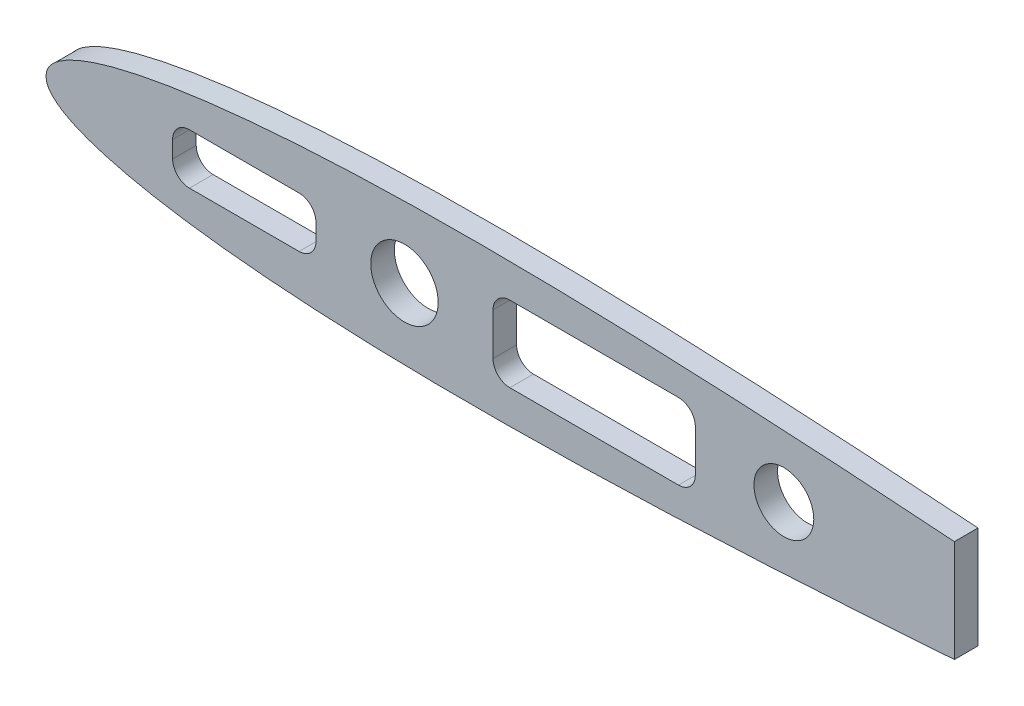
SolidWorks part; units mm, degrees
material "Фанера"
ref_plane "Front Plane" through (0, 0, 0) normal (0, 0, 1) x (1, 0, 0)
ref_plane "Top Plane" through (0, 0, 0) normal (0, 1, 0) x (1, 0, 0)
ref_plane "Right Plane" through (0, 0, 0) normal (1, 0, 0) x (0, 0, -1)
curve "Кривая1"
  spline degree 3 poles (110, 0, 0) (110.0276, -0.2367, 0) (110.0855, -0.7342, 0) (110.5302, -1.4271, 0) (111.1963, -2.0786, 0) (112.1098, -2.7013, 0) (113.2568, -3.2993, 0) (114.6379, -3.8731, 0) (116.2477, -4.4214, 0) (118.0813, -4.9426, 0) (120.1331, -5.4348, 0) (122.3972, -5.8961, 0) (124.8672, -6.3247, 0) (127.537, -6.7187, 0) (130.3997, -7.0764, 0) (133.4488, -7.3965, 0) (136.6771, -7.6776, 0) (140.0777, -7.9187, 0) (143.6433, -8.119, 0) (147.3662, -8.278, 0) (151.2389, -8.3955, 0) (155.2534, -8.4715, 0) (159.4016, -8.5065, 0) (163.6751, -8.501, 0) (168.0653, -8.456, 0) (172.5632, -8.3725, 0) (177.1595, -8.252, 0) (181.8446, -8.096, 0) (186.6087, -7.9062, 0) (191.4413, -7.6846, 0) (196.3316, -7.4331, 0) (201.2684, -7.1538, 0) (206.2396, -6.8489, 0) (211.233, -6.5205, 0) (216.2352, -6.1709, 0) (221.2323, -5.8022, 0) (226.2093, -5.417, 0) (231.1504, -5.0174, 0) (236.0382, -4.6058, 0) (240.8542, -4.1849, 0) (245.5777, -3.7574, 0) (250.1862, -3.3262, 0) (254.6542, -2.8948, 0) (258.9526, -2.4672, 0) (263.0477, -2.0479, 0) (266.899, -1.6426, 0) (270.4558, -1.2586, 0) (273.6512, -0.9053, 0) (276.3854, -0.5964, 0) (278.4526, -0.359, 0) (279.592, -0.2261, 0) (280, -0.1785, 0) knots 0 0 0 0 0.004099 0.008615 0.013935 0.020278 0.027753 0.03641 0.046266 0.05732 0.069559 0.082963 0.097507 0.113164 0.129903 0.14769 0.166492 0.186272 0.206992 0.228612 0.251092 0.274389 0.298458 0.323254 0.348728 0.37483 0.401509 0.42871 0.456376 0.484448 0.512864 0.541558 0.570462 0.599504 0.628607 0.65769 0.686667 0.715445 0.743924 0.771995 0.79954 0.826428 0.852512 0.877624 0.901571 0.924121 0.944989 0.963804 0.980044 0.992855 1 1 1 1
curve "Кривая2"
  spline degree 3 poles (280, 0.1785, 0) (279.592, 0.2261, 0) (278.4526, 0.359, 0) (276.3854, 0.5964, 0) (273.6512, 0.9053, 0) (270.4558, 1.2586, 0) (266.899, 1.6426, 0) (263.0477, 2.0479, 0) (258.9526, 2.4672, 0) (254.6542, 2.8948, 0) (250.1862, 3.3262, 0) (245.5777, 3.7574, 0) (240.8542, 4.1849, 0) (236.0382, 4.6058, 0) (231.1504, 5.0174, 0) (226.2093, 5.417, 0) (221.2323, 5.8022, 0) (216.2352, 6.1709, 0) (211.233, 6.5205, 0) (206.2396, 6.8489, 0) (201.2684, 7.1538, 0) (196.3316, 7.4331, 0) (191.4413, 7.6846, 0) (186.6087, 7.9062, 0) (181.8446, 8.096, 0) (177.1595, 8.252, 0) (172.5632, 8.3725, 0) (168.0653, 8.456, 0) (163.6751, 8.501, 0) (159.4016, 8.5065, 0) (155.2534, 8.4715, 0) (151.2389, 8.3955, 0) (147.3662, 8.278, 0) (143.6433, 8.119, 0) (140.0777, 7.9187, 0) (136.6771, 7.6776, 0) (133.4488, 7.3965, 0) (130.3997, 7.0764, 0) (127.537, 6.7187, 0) (124.8672, 6.3247, 0) (122.3972, 5.8961, 0) (120.1331, 5.4348, 0) (118.0813, 4.9426, 0) (116.2477, 4.4214, 0) (114.6379, 3.8731, 0) (113.2568, 3.2993, 0) (112.1098, 2.7013, 0) (111.1963, 2.0786, 0) (110.5302, 1.4271, 0) (110.0855, 0.7342, 0) (110.0276, 0.2367, 0) (110, 0, 0) knots 0 0 0 0 0.007145 0.019956 0.036196 0.055011 0.075879 0.098429 0.122376 0.147488 0.173572 0.20046 0.228005 0.256076 0.284555 0.313333 0.34231 0.371393 0.400496 0.429538 0.458442 0.487136 0.515552 0.543624 0.57129 0.598491 0.62517 0.651272 0.676746 0.701542 0.725611 0.748908 0.771388 0.793008 0.813728 0.833508 0.85231 0.870097 0.886836 0.902493 0.917037 0.930441 0.94268 0.953734 0.96359 0.972247 0.979722 0.986065 0.991385 0.995901 1 1 1 1
sketch "Эскиз1" plane through (0, 0, 0) normal (0, 0, 1) x (1, 0, 0)
  line L0 (105.1708, 0) -> (280.7263, 0) construction
  line L1 (280.0739, 0) -> (280.0739, 24.3846) construction
  line L2 (110, -5.3315) -> (110, 17.5304) construction
  line L3 (152.5185, 18.8331) -> (152.5185, -21.3473) construction
  line L4 (223.3826, 13.2402) -> (223.3826, -18.4275) construction
  line L5 (217.7476, 6.0581) -> (217.7476, -6.0581)
  line L6 (127.0185, -3) -> (140.0185, -3)
  line L7 (125.0185, -1) -> (125.0185, 1)
  line L8 (127.0185, 3) -> (140.0185, 3)
  line L9 (142.0185, -1) -> (142.0185, 1)
  line L10 (125.0185, -3) -> (142.0185, 3) construction
  line L11 (125.0185, 3) -> (142.0185, -3) construction
  line L12 (165.0185, -4.5) -> (185.0185, -4.5)
  line L13 (163.0185, -2.5) -> (163.0185, 2.5)
  line L14 (165.0185, 4.5) -> (185.0185, 4.5)
  line L15 (187.0185, -2.5) -> (187.0185, 2.5)
  line L16 (163.0185, -4.5) -> (187.0185, 4.5) construction
  line L17 (163.0185, 4.5) -> (187.0185, -4.5) construction
  arc A0 (280, 0.1785) -> (280, -0.1785) centre (279.8215, 0) cw
  circle A1 centre (152.5185, 0) radius 4
  circle A2 centre (197.5185, 0) radius 3.55
  arc A3 (185.0185, 4.5) -> (187.0185, 2.5) centre (185.0185, 2.5) cw
  arc A4 (185.0185, -4.5) -> (187.0185, -2.5) centre (185.0185, -2.5) ccw
  arc A5 (165.0185, -4.5) -> (163.0185, -2.5) centre (165.0185, -2.5) cw
  arc A6 (163.0185, 2.5) -> (165.0185, 4.5) centre (165.0185, 2.5) cw
  arc A7 (125.0185, 1) -> (127.0185, 3) centre (127.0185, 1) cw
  arc A8 (127.0185, -3) -> (125.0185, -1) centre (127.0185, -1) cw
  arc A9 (140.0185, -3) -> (142.0185, -1) centre (140.0185, -1) ccw
  arc A10 (140.0185, 3) -> (142.0185, 1) centre (140.0185, 1) cw
  arc A11 (223.3826, 5.635) -> (223.3826, -5.635) centre (223.3826, 0) ccw
  circle A12 centre (223.3826, 0) radius 1
  spline S0 degree 3 poles (-1802.3351, -584.8827) (164.5267, 33.7772) (105.6543, 6.1699) (110.5302, -1.4271) (111.1963, -2.0786) (112.1098, -2.7013) (113.2568, -3.2993) (114.6379, -3.8731) (116.2477, -4.4214) (118.0813, -4.9426) (120.1331, -5.4348) (122.3972, -5.8961) (124.8672, -6.3247) (127.537, -6.7187) (130.3997, -7.0764) (133.4488, -7.3965) (136.6771, -7.6776) (140.0777, -7.9187) (143.6433, -8.119) (147.3662, -8.278) (151.2389, -8.3955) (155.2534, -8.4715) (159.4016, -8.5065) (163.6751, -8.501) (168.0653, -8.456) (172.5632, -8.3725) (177.1595, -8.252) (181.8446, -8.096) (186.6087, -7.9062) (191.4413, -7.6846) (196.3316, -7.4331) (201.2684, -7.1538) (206.2396, -6.8489) (211.233, -6.5205) (216.2352, -6.1709) (221.2323, -5.8022) (226.2093, -5.417) (231.1504, -5.0174) (236.0382, -4.6058) (240.8542, -4.1849) (247.0711, -3.6222) (253.1161, -3.0479) (258.9526, -2.4672) (263.0477, -2.0479) (266.899, -1.6426) (270.4558, -1.2586) (273.6512, -0.9053) (276.3854, -0.5964) (359.5279, 8.955) (440.5611, 28.5776) (751.5392, -1938.3855) knots -0.13886 -0.13886 -0.13886 -0.13886 0.004099 0.008615 0.013935 0.020278 0.027753 0.03641 0.046266 0.05732 0.069559 0.082963 0.097507 0.113164 0.129903 0.14769 0.166492 0.186272 0.206992 0.228612 0.251092 0.274389 0.298458 0.323254 0.348728 0.37483 0.401509 0.42871 0.456376 0.484448 0.512864 0.541558 0.570462 0.599504 0.628607 0.65769 0.686667 0.715445 0.743924 0.771995 0.79954 0.852512 0.877624 0.901571 0.924121 0.944989 0.963804 0.980044 0.992855 2.419626 2.419626 2.419626 2.419626 only from (110, 0) to (280, -0.1785) construction
  spline S1 degree 3 poles (751.5383, 1938.3796) (440.561, -28.5775) (359.5279, -8.955) (276.3854, 0.5964) (273.6512, 0.9053) (270.4558, 1.2586) (266.899, 1.6426) (263.0477, 2.0479) (258.9526, 2.4672) (253.1161, 3.0479) (247.0711, 3.6222) (240.8542, 4.1849) (236.0382, 4.6058) (231.1504, 5.0174) (226.2093, 5.417) (221.2323, 5.8022) (216.2352, 6.1709) (211.233, 6.5205) (206.2396, 6.8489) (201.2684, 7.1538) (196.3316, 7.4331) (191.4413, 7.6846) (186.6087, 7.9062) (181.8446, 8.096) (177.1595, 8.252) (172.5632, 8.3725) (168.0653, 8.456) (163.6751, 8.501) (159.4016, 8.5065) (155.2534, 8.4715) (151.2389, 8.3955) (147.3662, 8.278) (143.6433, 8.119) (140.0777, 7.9187) (136.6771, 7.6776) (133.4488, 7.3965) (130.3997, 7.0764) (127.537, 6.7187) (124.8672, 6.3247) (122.3972, 5.8961) (120.1331, 5.4348) (118.0813, 4.9426) (116.2477, 4.4214) (114.6379, 3.8731) (113.2568, 3.2993) (112.1098, 2.7013) (111.1963, 2.0786) (110.5302, 1.4271) (105.6546, -6.1694) (164.5198, -33.7739) (-1801.974, 584.7691) knots -1.419625 -1.419625 -1.419625 -1.419625 0.007145 0.019956 0.036196 0.055011 0.075879 0.098429 0.122376 0.147488 0.20046 0.228005 0.256076 0.284555 0.313333 0.34231 0.371393 0.400496 0.429538 0.458442 0.487136 0.515552 0.543624 0.57129 0.598491 0.62517 0.651272 0.676746 0.701542 0.725611 0.748908 0.771388 0.793008 0.813728 0.833508 0.85231 0.870097 0.886836 0.902493 0.917037 0.930441 0.94268 0.953734 0.96359 0.972247 0.979722 0.986065 0.991385 0.995901 1.138851 1.138851 1.138851 1.138851 only from (280, 0.1785) to (110, 0) construction
  spline S2 degree 3 poles (110, 0) (110.0276, -0.2367) (110.0855, -0.7342) (110.5302, -1.4271) (111.1963, -2.0786) (112.1098, -2.7013) (113.2568, -3.2993) (114.6379, -3.8731) (116.2477, -4.4214) (118.0813, -4.9426) (120.1331, -5.4348) (122.3972, -5.8961) (124.8672, -6.3247) (127.537, -6.7187) (130.3997, -7.0764) (133.4488, -7.3965) (136.6771, -7.6776) (140.0777, -7.9187) (143.6433, -8.119) (147.3662, -8.278) (151.2389, -8.3955) (155.2534, -8.4715) (159.4016, -8.5065) (163.6751, -8.501) (168.0653, -8.456) (172.5632, -8.3725) (177.1595, -8.252) (181.8446, -8.096) (186.6087, -7.9062) (191.4413, -7.6846) (196.3316, -7.4331) (201.2684, -7.1538) (206.2396, -6.8489) (211.233, -6.5205) (216.2352, -6.1709) (221.2323, -5.8022) (226.2093, -5.417) (231.1504, -5.0174) (236.0382, -4.6058) (240.8542, -4.1849) (247.0711, -3.6222) (253.1161, -3.0479) (258.9526, -2.4672) (263.0477, -2.0479) (266.899, -1.6426) (270.4558, -1.2586) (273.6512, -0.9053) (276.3854, -0.5964) (278.4526, -0.359) (279.592, -0.2261) (280, -0.1785) knots 0 0 0 0 0.004099 0.008615 0.013935 0.020278 0.027753 0.03641 0.046266 0.05732 0.069559 0.082963 0.097507 0.113164 0.129903 0.14769 0.166492 0.186272 0.206992 0.228612 0.251092 0.274389 0.298458 0.323254 0.348728 0.37483 0.401509 0.42871 0.456376 0.484448 0.512864 0.541558 0.570462 0.599504 0.628607 0.65769 0.686667 0.715445 0.743924 0.771995 0.79954 0.852512 0.877624 0.901571 0.924121 0.944989 0.963804 0.980044 0.992855 1 1 1 1
  spline S3 degree 3 poles (280, 0.1785) (279.592, 0.2261) (278.4526, 0.359) (276.3854, 0.5964) (273.6512, 0.9053) (270.4558, 1.2586) (266.899, 1.6426) (263.0477, 2.0479) (258.9526, 2.4672) (253.1161, 3.0479) (247.0711, 3.6222) (240.8542, 4.1849) (236.0382, 4.6058) (231.1504, 5.0174) (226.2093, 5.417) (221.2323, 5.8022) (216.2352, 6.1709) (211.233, 6.5205) (206.2396, 6.8489) (201.2684, 7.1538) (196.3316, 7.4331) (191.4413, 7.6846) (186.6087, 7.9062) (181.8446, 8.096) (177.1595, 8.252) (172.5632, 8.3725) (168.0653, 8.456) (163.6751, 8.501) (159.4016, 8.5065) (155.2534, 8.4715) (151.2389, 8.3955) (147.3662, 8.278) (143.6433, 8.119) (140.0777, 7.9187) (136.6771, 7.6776) (133.4488, 7.3965) (130.3997, 7.0764) (127.537, 6.7187) (124.8672, 6.3247) (122.3972, 5.8961) (120.1331, 5.4348) (118.0813, 4.9426) (116.2477, 4.4214) (114.6379, 3.8731) (113.2568, 3.2993) (112.1098, 2.7013) (111.1963, 2.0786) (110.5302, 1.4271) (110.0855, 0.7342) (110.0276, 0.2367) (110, 0) knots 0 0 0 0 0.007145 0.019956 0.036196 0.055011 0.075879 0.098429 0.122376 0.147488 0.20046 0.228005 0.256076 0.284555 0.313333 0.34231 0.371393 0.400496 0.429538 0.458442 0.487136 0.515552 0.543624 0.57129 0.598491 0.62517 0.651272 0.676746 0.701542 0.725611 0.748908 0.771388 0.793008 0.813728 0.833508 0.85231 0.870097 0.886836 0.902493 0.917037 0.930441 0.94268 0.953734 0.96359 0.972247 0.979722 0.986065 0.991385 0.995901 1 1 1 1
  point P19 (175.0185, 0)
  point P22 (133.5185, 0)
  point P31 (223.3826, -5.635)
  point P54 (223.3826, 5.635)
  point P55 (223.3826, -5.635)
  point P56 (223.3826, 5.635)
  dimension "D1" = 0.2524
  dimension "D3" = 8
  dimension "D13" = 2
  dimension "D14" = 5.635
  dimension "D15" = 2
  dimension "D16" = 7.1
  dimension "D2" = 170.0739
  dimension "D4" = 42.5185
  dimension "D5" = 56.6913
  dimension "D6" = 45
  dimension "D7" = 6
  dimension "D8" = 17
  dimension "D9" = 19
  dimension "D10" = 22.5
  dimension "D11" = 9
  dimension "D12" = 24
extrude "Бобышка-Вытянуть1" add sketch "Эскиз1" along normal mid plane 2.8 contours L5 S3 S2 L8 A10 L9 A9 L6 A8 L7 A7 L13 A6 L14 A3 L15 A4 L12 A5 A1 A2
equation "\"D4@Эскиз1\"=\"D2@Эскиз1\"/4"
equation "\"D5@Эскиз1\"=\"D2@Эскиз1\"/3"
equation "\"D10@Эскиз1\"=\"D6@Эскиз1\"/2"
